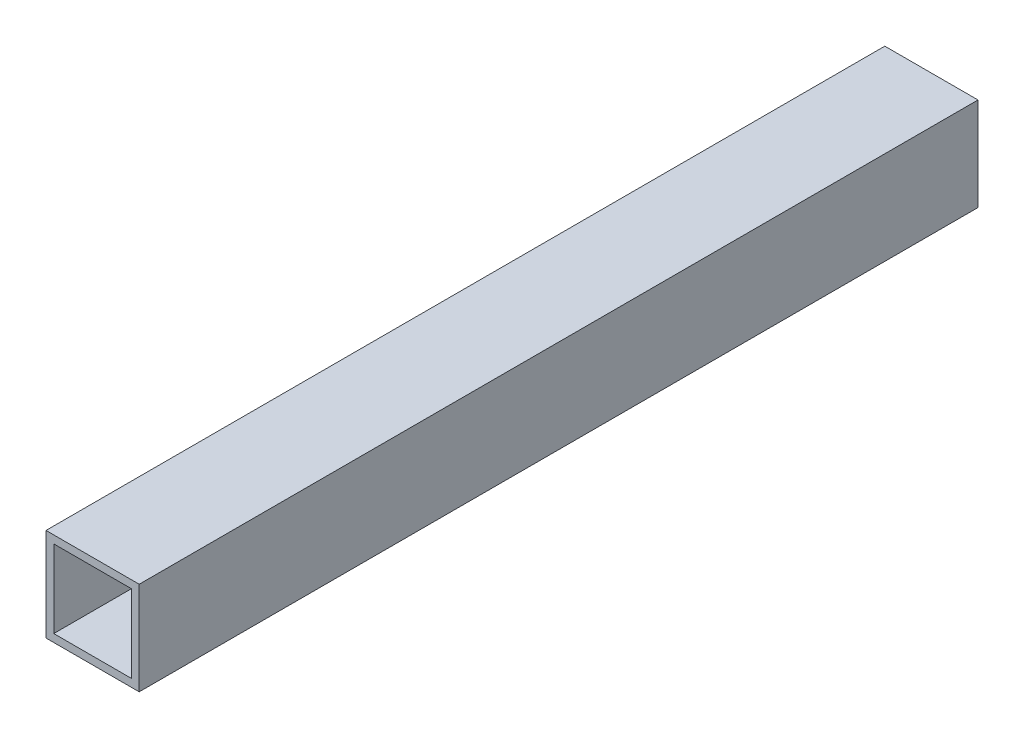
SolidWorks part; units mm, degrees
ref_plane "前视基准面" through (0, 0, 0) normal (0, 0, 1) x (1, 0, 0)
ref_plane "上视基准面" through (0, 0, 0) normal (0, 1, 0) x (1, 0, 0)
ref_plane "右视基准面" through (0, 0, 0) normal (1, 0, 0) x (0, 0, -1)
sketch "草图1" plane through (0, 0, 0) normal (0, 0, 1) x (1, 0, 0)
  line L0 (-12, 12) -> (12, 12)
  line L1 (-10, 10) -> (10, 10)
  line L2 (-10, 10) -> (-10, -10)
  line L3 (-10, -10) -> (10, -10)
  line L4 (10, 10) -> (10, -10)
  line L5 (-10, 10) -> (10, -10) construction
  line L6 (-10, -10) -> (10, 10) construction
  line L7 (12, 12) -> (12, -12)
  line L8 (-12, -12) -> (12, -12)
  line L9 (-12, 12) -> (-12, -12)
  point P0 (0, 0)
  dimension "D1" = 20
  dimension "D2" = 20
  dimension "D3" = 2
extrude "凸台-拉伸1" add sketch "草图1" along normal mid plane 216
